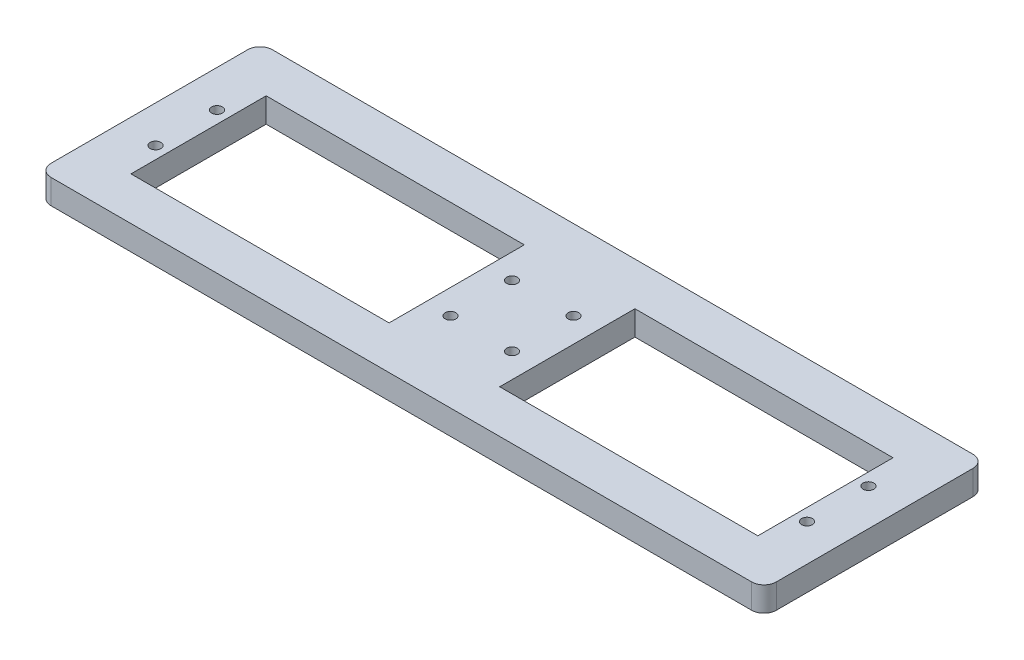
SolidWorks part; units mm, degrees
ref_plane "Front Plane" through (0, 0, 0) normal (0, 0, 1) x (1, 0, 0)
ref_plane "Top Plane" through (0, 0, 0) normal (0, 1, 0) x (1, 0, 0)
ref_plane "Right Plane" through (0, 0, 0) normal (1, 0, 0) x (0, 0, -1)
sketch "Sketch2" plane through (0, 0, 0) normal (0, 1, 0) x (1, 0, 0)
  line L0 (0, 30.0654) -> (0, -24.8665) construction
  line L1 (-57, 18) -> (57, 18)
  line L2 (-59, 16) -> (-59, -16)
  line L3 (-57, -18) -> (57, -18)
  line L4 (59, 16) -> (59, -16)
  line L5 (-59, 18) -> (59, -18) construction
  line L6 (-59, -18) -> (59, 18) construction
  line L7 (-51, 11) -> (-9, 11)
  line L8 (-51, 11) -> (-51, -11)
  line L9 (-51, -11) -> (-9, -11)
  line L10 (-9, 11) -> (-9, -11)
  line L11 (-51, 11) -> (-9, -11) construction
  line L12 (-51, -11) -> (-9, 11) construction
  line L13 (51, -11) -> (9, -11)
  line L14 (9, 11) -> (9, -11)
  line L15 (51, 11) -> (51, -11)
  line L16 (51, 11) -> (9, 11)
  line L17 (-88.3925, 0) -> (81.0122, 0) construction
  arc A0 (57, -18) -> (59, -16) centre (57, -16) ccw
  arc A1 (57, 18) -> (59, 16) centre (57, 16) cw
  arc A2 (-59, -16) -> (-57, -18) centre (-57, -16) ccw
  arc A3 (-57, 18) -> (-59, 16) centre (-57, 16) ccw
  point P0 (0, 0)
  point P6 (-30, 0)
  dimension "D7" = 2
  dimension "D1" = 36
  dimension "D2" = 118
  dimension "D3" = 42
  dimension "D4" = 22
  dimension "D6" = 8
extrude "Boss-Extrude1" add sketch "Sketch2" along normal blind 4
sketch "Sketch3" plane through (0, 0, 0) normal (0, -1, 0) x (1, 0, 0)
  circle A0 centre (-53, 5) radius 0.875
  circle A1 centre (-53, -5) radius 0.875
  dimension "D1" = 1.75
  dimension "D2" = 1.75
extrude "Cut-Extrude1" cut sketch "Sketch3" against normal blind 10
sketch "Sketch4" plane through (0, 0, 0) normal (0, -1, 0) x (1, 0, 0)
  circle A0 centre (-5, 5) radius 0.875
  circle A1 centre (-5, -5) radius 0.875
  dimension "D1" = 1.75
  dimension "D2" = 1.75
extrude "Cut-Extrude2" cut sketch "Sketch4" against normal blind 10
mirror "Mirror1" about plane through (0, 0, 0) normal (1, 0, 0) of "Cut-Extrude2", "Cut-Extrude1"
